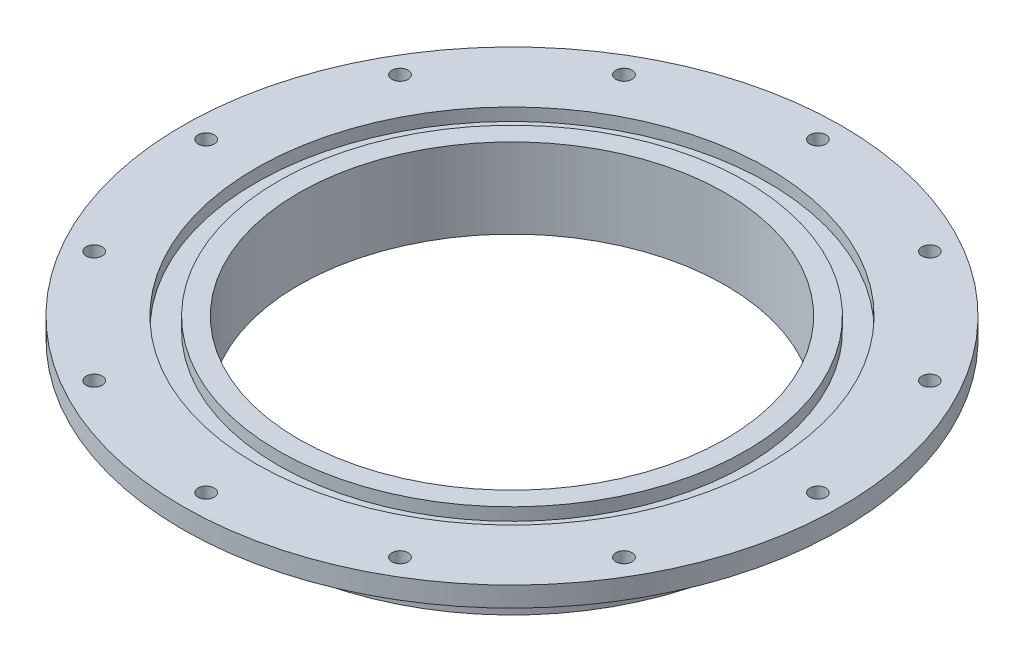
SolidWorks part; units mm, degrees
ref_plane "Front Plane" through (0, 0, 0) normal (0, 0, 1) x (1, 0, 0)
ref_plane "Top Plane" through (0, 0, 0) normal (0, 1, 0) x (1, 0, 0)
ref_plane "Right Plane" through (0, 0, 0) normal (1, 0, 0) x (0, 0, -1)
sketch "Sketch1" plane through (0, 0, 0) normal (0, 1, 0) x (1, 0, 0)
  circle A0 centre (0, 0) radius 80.518
  circle A1 centre (0, 0) radius 67.818
  dimension "D1" = 161.036
  dimension "D2" = 12.7
extrude "Inner Cylinder" add sketch "Sketch1" along normal blind 19.05
sketch "Sketch2" plane through (0, 19.05, 0) normal (0, 1, 0) x (1, 0, 0)
  circle A0 centre (0, 0) radius 67.818
  circle A1 centre (0, 0) radius 67.818 construction
  circle A2 centre (0, 0) radius 104.775
  dimension "D1" = 209.55
extrude "Flange" add sketch "Sketch2" along normal blind 6.35
sketch "Sketch4" plane through (0, 25.4, 0) normal (0, 1, 0) x (1, 0, 0)
  line L0 (0, 75.8825) -> (0, 81.2165) construction
  circle A3 centre (0, 0) radius 81.407
  circle A4 centre (0, 0) radius 74.295
  point P7 (0, 78.5495)
  dimension "D1" = 148.59
  dimension "D2" = 7.112
  dimension "D3" = 2.667
extrude "Groove" cut sketch "Sketch4" against normal blind 3.9878
sketch "Sketch5" plane through (0, 25.4, 0) normal (0, 1, 0) x (1, 0, 0)
  line L0 (89.7255, 0) -> (104.775, 0) construction
  circle A0 centre (0, 0) radius 97.2503 construction
  circle A1 centre (0, -97.2503) radius 3.175 construction
  circle A3 centre (0, -97.2503) radius 2.5527
  circle A6 centre (0, 0) radius 89.7255 construction
  circle A7 centre (0, 0) radius 104.775 construction
  point P9 (97.2503, 0)
  dimension "D1" = 5.1054
  dimension "D2" = 179.451
  dimension "D3" = 6.35
extrude "Screw Holes" cut sketch "Sketch5" against normal up to surface (6.35 mm away) up to face at (0, 19.05, 80.518)
pattern_circular "CirPattern1" count 12 over 360 about axis through (0, 0, 0) along (0, 1, 0) of "Screw Holes"
sketch "Sketch6" plane through (0, 25.4, 0) normal (0, 1, 0) x (1, 0, 0)
  circle A0 centre (0, 0) radius 89.7255
  dimension "D1" = 179.451
